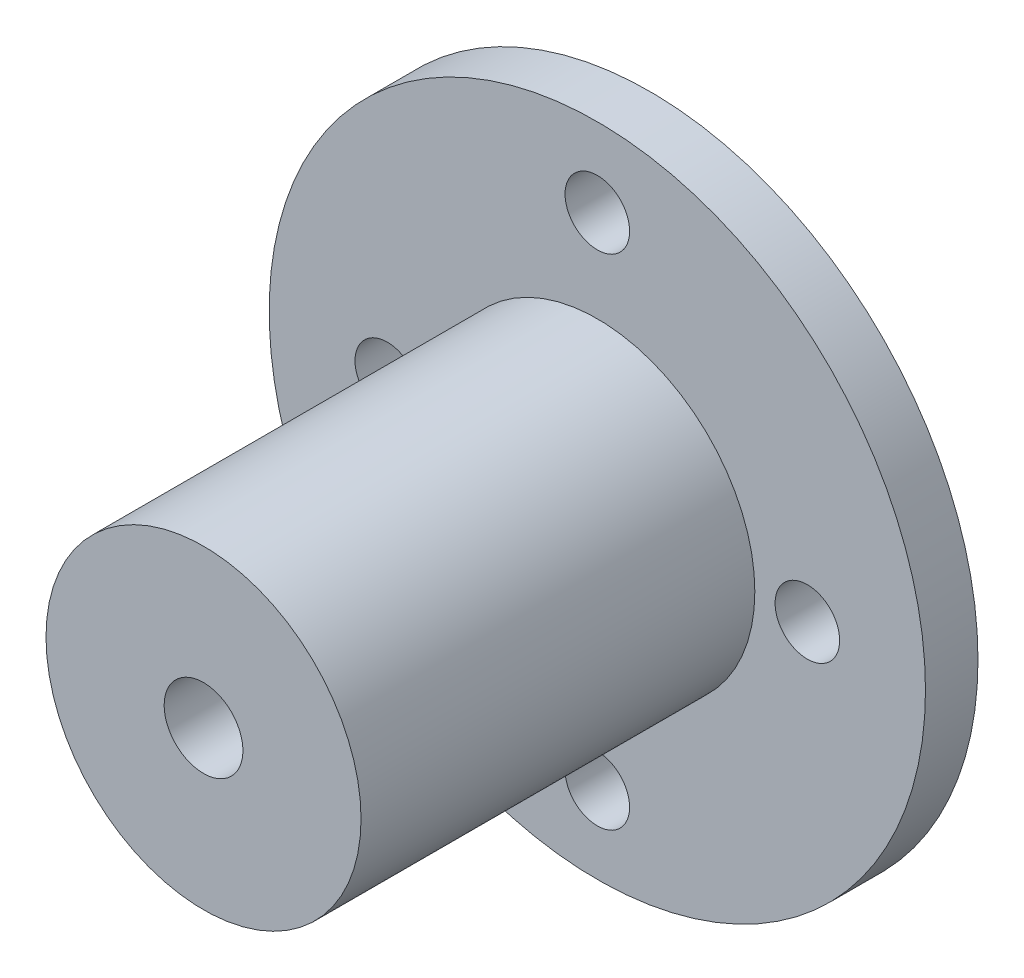
SolidWorks part; units mm, degrees
ref_plane "Plan de face" through (0, 0, 0) normal (0, 0, 1) x (1, 0, 0)
ref_plane "Plan de dessus" through (0, 0, 0) normal (0, 1, 0) x (1, 0, 0)
ref_plane "Plan de droite" through (0, 0, 0) normal (1, 0, 0) x (0, 0, -1)
ref_plane "Plan1" through (0, 152.7028, 0) normal (0, 1, 0) x (1, 0, 0)
sketch "Esquisse1" plane through (0, 152.7028, 0) normal (0, 1, 0) x (1, 0, 0)
  line L0 (183.6708, 0) -> (171.1708, 0)
  line L1 (171.1708, 0) -> (171.1708, -2)
  line L2 (171.1708, -2) -> (183.6708, -2)
  line L3 (183.6708, -2) -> (183.6708, 0)
  line L4 (171.1708, 0) -> (171.1708, -2) construction
revolve "Révolution1" add sketch "Esquisse1" angle 360 about L4
sketch "Esquisse2" plane through (0, 0, 2) normal (0, 0, 1) x (1, 0, 0)
  circle A0 centre (171.1708, 152.7028) radius 6
extrude "Boss.-Extru.1" add sketch "Esquisse2" along normal blind 15
hole_wizard "Diamètre du perçage Ø3.0 (3)1" positions "Esquisse4" profile "Esquisse3" hole size "Ø3.0" standard "Ansi Metric"
sketch "Esquisse4" plane through (0, 0, 0) normal (0, 0, -1) x (-1, 0, 0)
  point P0 (-171.1708, 152.7028)
sketch "Esquisse3" plane through (171.1708, 152.7028, 0) normal (1, 0, 0) x (0, 1, 0)
  line L0 (0, 0) -> (0, 17)
  line L1 (0, 17) -> (1.5, 17)
  line L2 (1.5, 17) -> (1.5, 0)
  line L5 (1.5, 0) -> (0, 0)
  line L11 (0, -6.35) -> (0, 107.95) construction
  dimension "Diamètre du perçage jusqu'au prochain" = 3
  dimension "Profondeur du perçage jusqu'au prochain" = 17
hole_wizard "Dégagement M21" positions "Esquisse6" profile "Esquisse5" hole size "M2" standard "Ansi Metric"
sketch "Esquisse6" plane through (0, 0, 0) normal (0, 0, -1) x (-1, 0, 0)
  point P0 (-179.1708, 152.7028)
  point P1 (-163.1708, 152.7028)
  point P2 (-171.1708, 162.2028)
  point P3 (-171.1708, 143.2028)
sketch "Esquisse5" plane through (179.1708, 152.7028, 0) normal (1, 0, 0) x (0, 1, 0)
  line L0 (0, 0) -> (0, 17)
  line L1 (0, 17) -> (1.2295, 17)
  line L2 (1.2295, 17) -> (1.2295, 0)
  line L5 (1.2295, 0) -> (0, 0)
  line L11 (0, -6.35) -> (0, 107.95) construction
  dimension "Diamètre du perçage jusqu'au prochain" = 2.459
  dimension "Profondeur du perçage jusqu'au prochain" = 17
